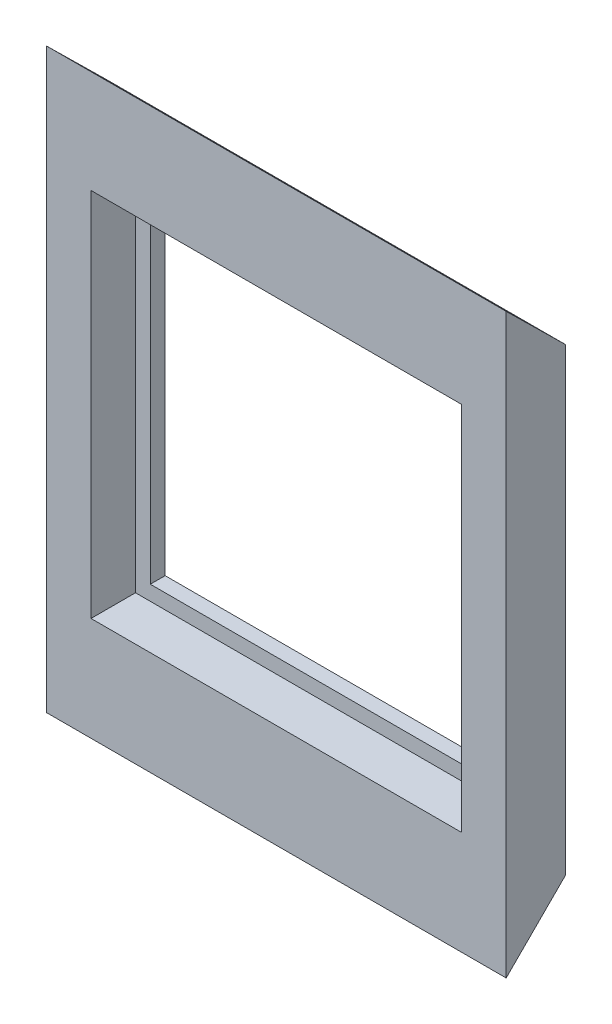
SolidWorks part; units mm, degrees
ref_plane "Front Plane" through (0, 0, 0) normal (0, 0, 1) x (1, 0, 0)
ref_plane "Top Plane" through (0, 0, 0) normal (0, 1, 0) x (1, 0, 0)
ref_plane "Right Plane" through (0, 0, 0) normal (1, 0, 0) x (0, 0, -1)
sketch "Sketch3" plane through (0, 0, 0) normal (0, 0, 1) x (1, 0, 0)
  line L1 (-15.5, -15.5) -> (15.5, -15.5)
  line L2 (-15.5, -15.5) -> (-15.5, 15.5)
  line L3 (-15.5, 15.5) -> (15.5, 15.5)
  line L4 (15.5, -15.5) -> (15.5, 15.5)
  line L5 (-15.5, -15.5) -> (15.5, 15.5) construction
  line L6 (-15.5, 15.5) -> (15.5, -15.5) construction
  point P0 (0, 0)
  dimension "D1" = 31
  dimension "D2" = 31
extrude "Boss-Extrude2" add sketch "Sketch3" along normal blind 4
sketch "Sketch4" plane through (0, 0, 4) normal (0, 0, 1) x (1, 0, 0)
  line L1 (-12.5, -12.5) -> (12.5, -12.5)
  line L2 (-12.5, -12.5) -> (-12.5, 12.5)
  line L3 (-12.5, 12.5) -> (12.5, 12.5)
  line L4 (12.5, -12.5) -> (12.5, 12.5)
  line L5 (-12.5, -12.5) -> (12.5, 12.5) construction
  line L6 (-12.5, 12.5) -> (12.5, -12.5) construction
  point P0 (0, 0)
  dimension "D1" = 25
  dimension "D2" = 25
extrude "Cut-Extrude1" cut sketch "Sketch4" against normal blind 3
sketch "Sketch5" plane through (0, 0, 1) normal (0, 0, 1) x (1, 0, 0)
  line L1 (-11.5, -11.5) -> (11.5, -11.5)
  line L2 (-11.5, -11.5) -> (-11.5, 11.5)
  line L3 (-11.5, 11.5) -> (11.5, 11.5)
  line L4 (11.5, -11.5) -> (11.5, 11.5)
  line L5 (-11.5, -11.5) -> (11.5, 11.5) construction
  line L6 (-11.5, 11.5) -> (11.5, -11.5) construction
  point P0 (0, 0)
  dimension "D1" = 23
  dimension "D2" = 23
extrude "Cut-Extrude2" cut sketch "Sketch5" against normal blind 5
sketch "Sketch6" plane through (-15.5, 0, 0) normal (-1, 0, 0) x (0, 0, 1)
  line L0 (4, -15.5) -> (4, -19.5)
  line L1 (4, -19.5) -> (0, -15.5)
  line L2 (0, -15.5) -> (4, -15.5)
sweep "Sweep1" add profiles "Sketch6" path edge at (0, -15.5, 4)
sketch "Sketch8" plane through (-15.5, 0, 0) normal (-1, 0, 0) x (0, 0, 1)
  line L0 (0, 15.5) -> (4, 19.4363)
  line L1 (0, 15.5) -> (0, -15.5) construction
  line L2 (4, 15.5) -> (0, 15.5) construction
  line L3 (4, 19.4363) -> (4, 15.5)
  line L4 (4, 15.5) -> (4, -19.5) construction
  line L5 (4, 15.5) -> (0, 15.5)
sweep "Sweep2" add profiles "Sketch8" path edge at (0, 15.5, 0)
